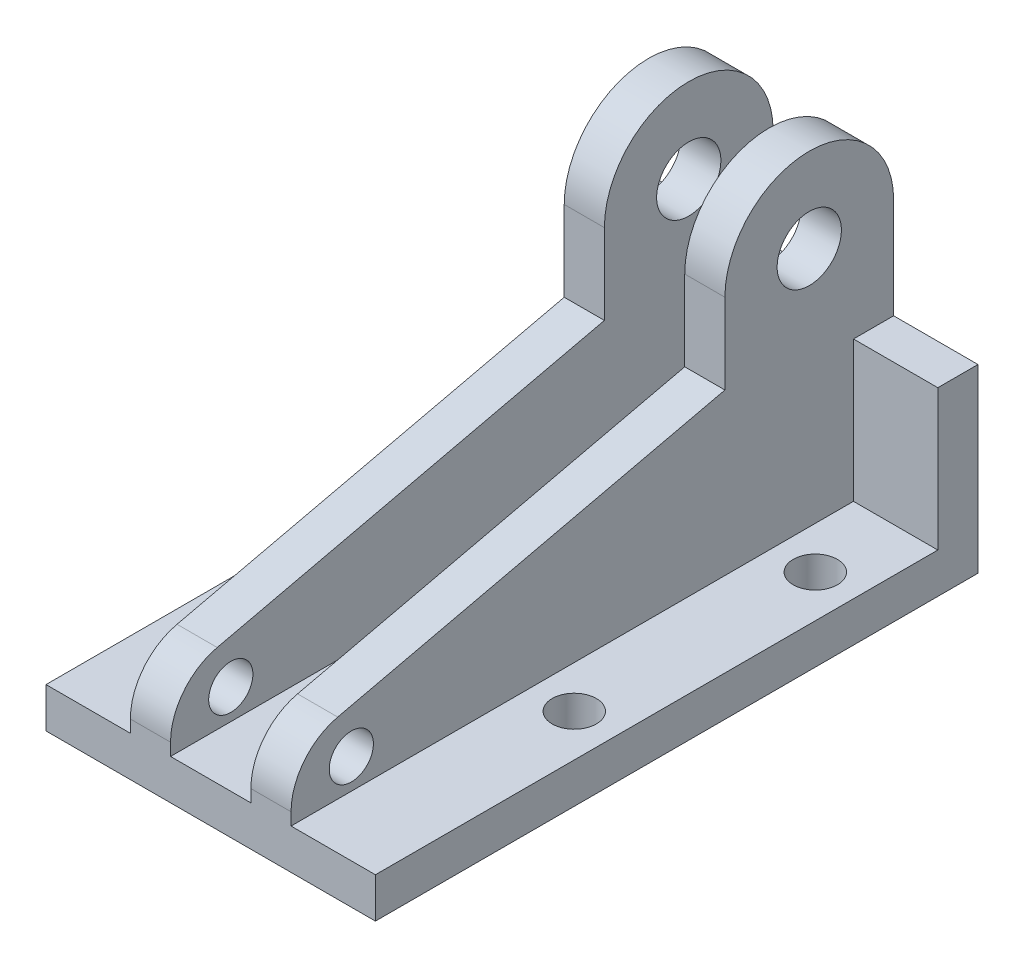
SolidWorks part; units mm, degrees
other "Markup1"
sketch "Sketch5" plane through (41, 46, 150) normal (0.5774, 0.5773, 0.5774) x (0.7071, 0, -0.7071)
material "Alloy Steel"
ref_plane "Front Plane" through (0, 0, 0) normal (0, 0, 1) x (1, 0, 0)
ref_plane "Top Plane" through (0, 0, 0) normal (0, 1, 0) x (1, 0, 0)
ref_plane "Right Plane" through (0, 0, 0) normal (1, 0, 0) x (0, 0, -1)
sketch "Sketch1" plane through (0, 0, 0) normal (1, 0, 0) x (0, 0, -1)
  line L1 (0, 0) -> (-10, 0)
  line L2 (0, 0) -> (0, -45)
  line L4 (-10, 0) -> (-10, -35)
  line L5 (0, -45) -> (-150, -45)
  line L7 (-10, -35) -> (-150, -35)
  line L8 (-150, -45) -> (-150, -35)
  point P8 (-2.2613, -34.108)
  dimension "D1" = 150
  dimension "D2" = 45
  dimension "D3" = 10
  dimension "D4" = 10
extrude "Boss-Extrude1" add sketch "Sketch1" along normal mid plane 82
ref_plane "Plane1" through (10, 0, 0) normal (1, 0, 0) x (0, 0, -1)
sketch "Sketch2" plane through (10, 0, 0) normal (1, 0, 0) x (0, 0, -1)
  line L0 (-10, -35) -> (-150, -35) construction
  line L1 (-150, -35) -> (-150, -45) construction
  line L2 (-150, -35) -> (-150, -20)
  line L3 (-150, -20) -> (-42, 5)
  line L4 (-42, 25) -> (-42, 5)
  line L5 (0, 25) -> (0, 0)
  line L6 (0, -45) -> (0, 0) construction
  line L7 (-150, -45) -> (0, -45) construction
  line L8 (-150, -35) -> (-10, -35)
  line L9 (-10, 0) -> (-10, -35) construction
  line L10 (-10, -35) -> (-10, 0)
  line L11 (-10, 0) -> (0, 0)
  arc A0 (0, 25) -> (-42, 25) centre (-21, 25) ccw
  circle A1 centre (-21, 25) radius 8
  circle A2 centre (-135, -27.5) radius 5.5
  point P1 (-154.8966, -15.7664)
  point P14 (0, 0)
  point P25 (-150, -14.8657)
  point P28 (0, 0)
  dimension "D1" = 11
  dimension "D2" = 42
  dimension "D3" = 16
  dimension "D5" = 25
  dimension "D4" = 7.5
  dimension "D6" = 15
  dimension "D7" = 40
  dimension "D8" = 70
extrude "Boss-Extrude2" add sketch "Sketch2" along normal blind 10
mirror "Mirror1" about plane through (0, 0, 0) normal (1, 0, 0) of "Boss-Extrude2"
sketch "Sketch3" plane through (0, -35, 0) normal (0, 1, 0) x (1, 0, 0)
  line L0 (41, 0) -> (20, 0) construction
  line L2 (41, -150) -> (20, -150) construction
  line L3 (-20, -150) -> (-41, -150) construction
  circle A0 centre (30.5, -30) radius 5.5
  circle A1 centre (30.5, -90) radius 5.5
  circle A2 centre (-30.5, -90) radius 5.5
  circle A3 centre (-30.5, -30) radius 5.5
  point P8 (0, 0)
  point P9 (0, 0)
  point P16 (30.5, -150)
  point P17 (-30.5, -150)
  dimension "D1" = 11
  dimension "D2" = 60
  dimension "D3" = 30
extrude "Cut-Extrude1" cut sketch "Sketch3" against normal blind 10
fillet "Fillet1" radius 15 2 edges at (-15, -20, 150) (15, -20, 150)
